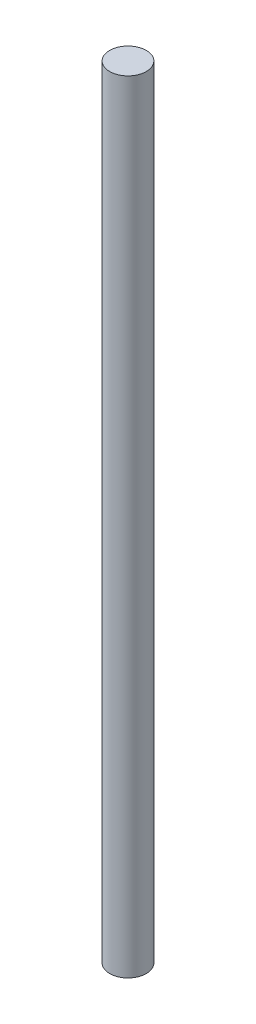
SolidWorks part; units mm, degrees
ref_plane "前视基准面" through (0, 0, 0) normal (0, 0, 1) x (1, 0, 0)
ref_plane "上视基准面" through (0, 0, 0) normal (0, 1, 0) x (1, 0, 0)
ref_plane "右视基准面" through (0, 0, 0) normal (1, 0, 0) x (0, 0, -1)
other "Configuration Table"
sketch "草图1" plane through (0, 0, 0) normal (0, 1, 0) x (1, 0, 0)
  circle A0 centre (0, 0) radius 1.5
  dimension "D1" = 3
extrude "凸台-拉伸1" add sketch "草图1" along normal blind 64
